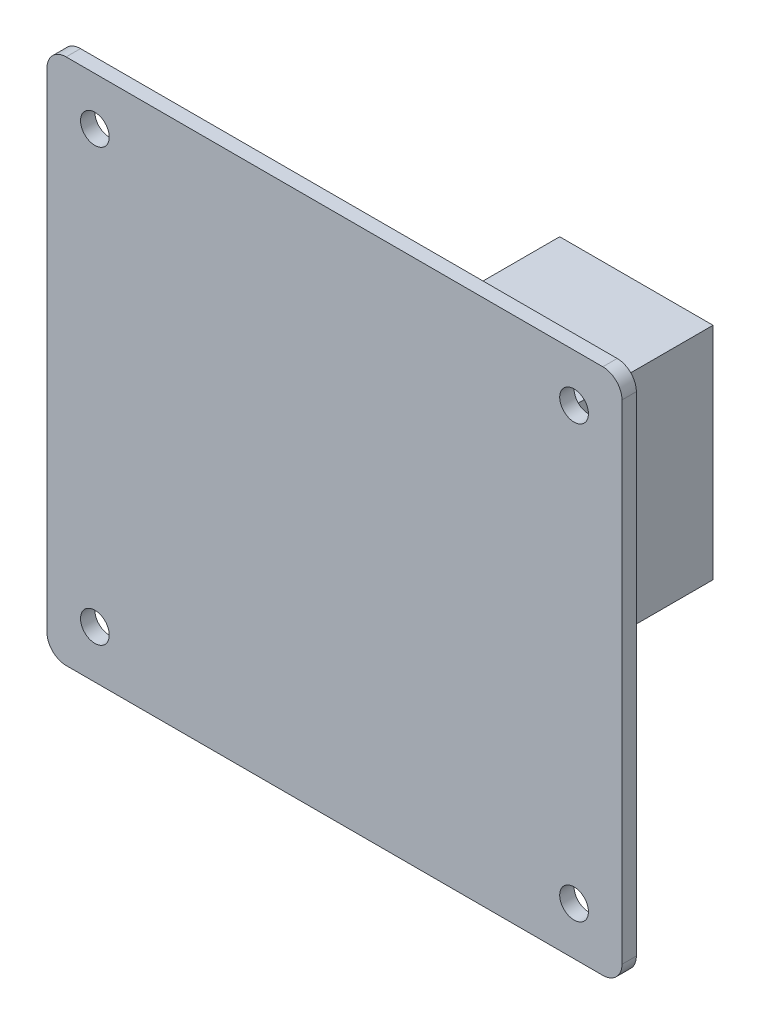
SolidWorks part; units mm, degrees
ref_plane "Plan de face" through (0, 0, 0) normal (0, 0, 1) x (1, 0, 0)
ref_plane "Plan de dessus" through (0, 0, 0) normal (0, 1, 0) x (1, 0, 0)
ref_plane "Plan de droite" through (0, 0, 0) normal (1, 0, 0) x (0, 0, -1)
sketch "Esquisse1" plane through (0, 0, 0) normal (0, 0, 1) x (1, 0, 0)
  line L1 (0, 0) -> (60, 0)
  line L2 (0, 0) -> (0, 55)
  line L3 (0, 55) -> (60, 55)
  line L4 (60, 0) -> (60, 55)
  dimension "D1" = 60
  dimension "D2" = 55
extrude "Boss.-Extru.1" add sketch "Esquisse1" along normal blind 1.5
fillet "Congé1" radius 2 4 edges at (60, 0, 0.75) (60, 55, 0.75) (0, 55, 0.75) (0, 0, 0.75)
sketch "Esquisse2" plane through (0, 0, 0) normal (0, 0, -1) x (-1, 0, 0)
  line L0 (-55, 50) -> (-5, 50) construction
  line L1 (-5, 50) -> (-5, 5) construction
  line L2 (-5, 5) -> (-55, 5) construction
  line L3 (-55, 5) -> (-55, 50) construction
  line L4 (0, 53) -> (0, 2) construction
  line L5 (-58, 55) -> (-2, 55) construction
  circle A0 centre (-5, 5) radius 1.5
  circle A1 centre (-5, 50) radius 1.5
  circle A2 centre (-55, 50) radius 1.5
  circle A3 centre (-55, 5) radius 1.5
  dimension "D5" = 3
  dimension "D6" = 3
  dimension "D7" = 3
  dimension "D8" = 3
  dimension "D1" = 50
  dimension "D2" = 45
  dimension "D3" = 5
  dimension "D4" = 5
extrude "Enlèv. mat.-Extru.1" cut sketch "Esquisse2" against normal blind 1.5
sketch "Esquisse3" plane through (0, 0, 0) normal (0, 0, -1) x (-1, 0, 0)
  line L0 (-2, 0) -> (-58, 0) construction
  line L1 (-43, 38) -> (-27, 38)
  line L2 (-43, 38) -> (-43, 15)
  line L3 (-43, 15) -> (-27, 15)
  line L4 (-27, 38) -> (-27, 15)
  line L7 (0, 53) -> (0, 2) construction
  dimension "D1" = 16
  dimension "D2" = 23
  dimension "D3" = 15
  dimension "D4" = 27
extrude "Boss.-Extru.2" add sketch "Esquisse3" along normal blind 25
